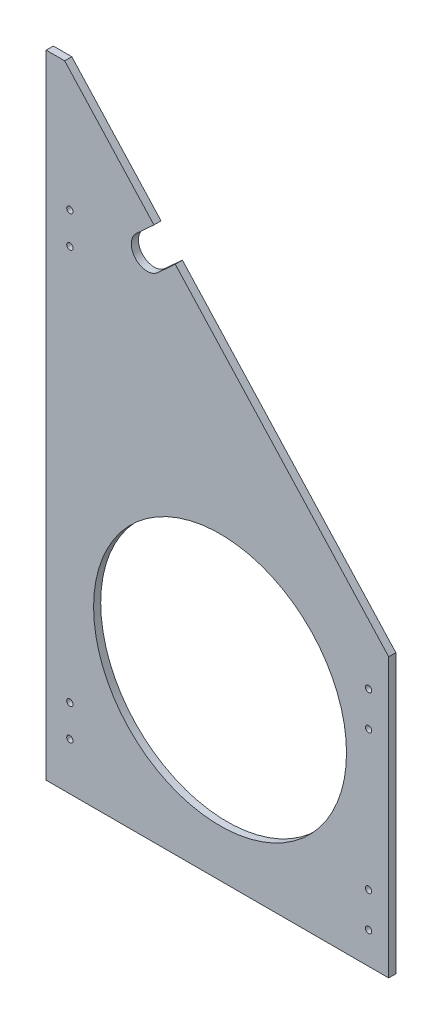
SolidWorks part; units mm, degrees
material "ABS PC"
ref_plane "前视基准面" through (0, 0, 0) normal (0, 0, 1) x (1, 0, 0)
ref_plane "上视基准面" through (0, 0, 0) normal (0, 1, 0) x (1, 0, 0)
ref_plane "右视基准面" through (0, 0, 0) normal (1, 0, 0) x (0, 0, -1)
sketch "草图1" plane through (0, 0, 0) normal (0, 0, 1) x (1, 0, 0)
  line L0 (0, 0) -> (216.7, 0)
  line L1 (216.7, 0) -> (216.7, 176)
  line L2 (216.7, 176) -> (11.7, 400)
  line L3 (0, 400) -> (0, 0)
  line L4 (110, 0) -> (110, 238.7949) construction
  line L5 (0, 400) -> (11.7, 400)
  line L6 (0, 400) -> (0, 412.7844) construction
  line L7 (0, 412.7844) -> (11.7, 400) construction
  circle A0 centre (110, 110) radius 80
  circle A1 centre (110, 110) radius 90 construction
  dimension "D4" = 160
  dimension "D6" = 180
  dimension "D7" = 110
  dimension "D1" = 400
  dimension "D2" = 216.7
  dimension "D3" = 176
  dimension "D5" = 110
  dimension "D8" = 11.7
extrude "凸台-拉伸1" add sketch "草图1" along normal blind 4.5
sketch "草图2" plane through (0, 0, 4.5) normal (0, 0, 1) x (1, 0, 0)
  line L0 (203.95, 0) -> (203.95, 170.9337) construction
  line L1 (0, 0) -> (216.7, 0) construction
  line L2 (216.7, 0) -> (216.7, 176) construction
  line L3 (15, 0) -> (15, 373.0421) construction
  line L4 (0, 400) -> (0, 0) construction
  line L5 (57.1064, 328.1672) -> (68.1719, 338.2942)
  line L6 (216.7, 176) -> (11.7, 400) construction
  line L7 (70.6089, 313.4132) -> (81.6744, 323.5401)
  line L8 (68.1719, 338.2942) -> (81.6744, 323.5401)
  circle A0 centre (203.95, 20) radius 2
  circle A1 centre (203.95, 42) radius 2
  circle A2 centre (203.95, 130) radius 2
  circle A3 centre (203.95, 152) radius 2
  circle A4 centre (15, 30) radius 2
  circle A5 centre (15, 50) radius 2
  circle A6 centre (15, 300) radius 2
  circle A7 centre (15, 320) radius 2
  arc A8 (57.1064, 328.1672) -> (70.6089, 313.4132) centre (63.8576, 320.7902) ccw
  dimension "D1" = 4
  dimension "D7" = 4
  dimension "D13" = 20
  dimension "D2" = 22
  dimension "D3" = 22
  dimension "D4" = 12.75
  dimension "D5" = 20
  dimension "D6" = 110
  dimension "D8" = 20
  dimension "D9" = 20
  dimension "D10" = 30
  dimension "D11" = 300
  dimension "D12" = 15
  dimension "D14" = 15
  dimension "D15" = 200
extrude "切除-拉伸1" cut sketch "草图2" against normal up to next
